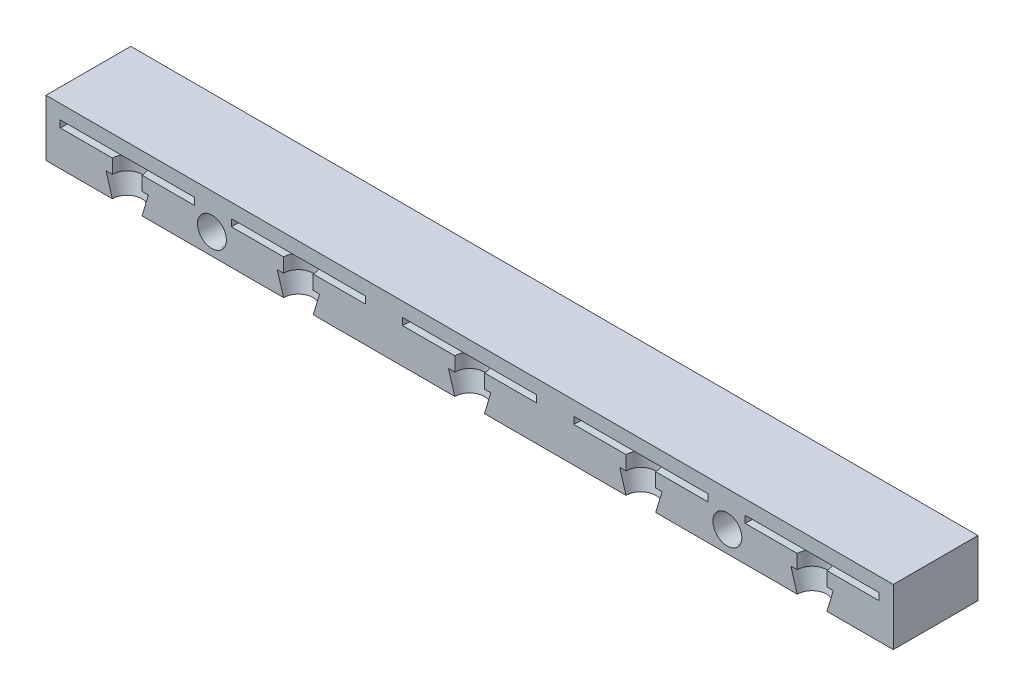
SolidWorks part; units mm, degrees
ref_plane "Front Plane" through (0, 0, 0) normal (0, 0, 1) x (1, 0, 0)
ref_plane "Top Plane" through (0, 0, 0) normal (0, 1, 0) x (1, 0, 0)
ref_plane "Right Plane" through (0, 0, 0) normal (1, 0, 0) x (0, 0, -1)
sketch "Sketch2" plane through (0, 0, 0) normal (0, 0, 1) x (1, 0, 0)
  line L1 (0, 0) -> (120, 0)
  line L2 (0, 0) -> (0, 8)
  line L3 (0, 8) -> (120, 8)
  line L4 (120, 0) -> (120, 8)
  dimension "D1" = 8
  dimension "D2" = 120
extrude "Boss-Extrude1" add sketch "Sketch2" against normal blind 12
sketch "Sketch3" plane through (0, 0, 0) normal (0, 0, 1) x (1, 0, 0)
  line L1 (0, 8) -> (0, 0) construction
  line L2 (8.5, 3) -> (9.4, 3)
  line L3 (9.4, 3) -> (9.4, 5)
  line L4 (9.4, 5) -> (2, 5)
  line L7 (11.5, 6) -> (11.5, 0) construction
  line L8 (8.5, 3) -> (9.4, 0)
  line L9 (9.4, 0) -> (11.5, 0)
  line L10 (0, 0) -> (120, 0) construction
  line L11 (11.5, 0) -> (11.5, 6)
  line L12 (2, 5) -> (2, 6)
  line L13 (2, 6) -> (11.5, 6)
  dimension "D1" = 2
  dimension "D2" = 0
  dimension "D3" = 2.1
  dimension "D4" = 3
  dimension "D5" = 1
  dimension "D6" = 3
  dimension "D7" = 2.1
  dimension "D8" = 0
  dimension "D9" = 2
  dimension "D10" = 9.5
revolve "Cut-Revolve1" cut sketch "Sketch3" angle 360 about L7
pattern_linear "LPattern1" count 5 spacing 24.25 along (1, 0, 0) of "Cut-Revolve1"
sketch "Sketch4" plane through (0, 0, 0) normal (0, 0, 1) x (1, 0, 0)
  line L0 (21, 8) -> (2, 8) construction
  line L1 (11.5, 0) -> (11.5, 8) construction
  line L2 (9.4, 0) -> (13.6, 0) construction
  line L3 (120, 0) -> (120, 8) construction
  line L4 (0, 0) -> (9.4, 0) construction
  line L7 (0, 0) -> (9.4, 0) construction
  circle A0 centre (23.5, 3) radius 2.05
  circle A2 centre (96.5, 3) radius 2.05
  dimension "D2" = 4.1
  dimension "D1" = 23.5
  dimension "D3" = 3
  dimension "D4" = 23.5
  dimension "D5" = 3
extrude "Cut-Extrude1" cut sketch "Sketch4" against normal blind 5 draft 1
equation "\"D4@Sketch4\"=\"D1@Sketch4\""
equation "\"D5@Sketch4\"=\"D3@Sketch4\""
